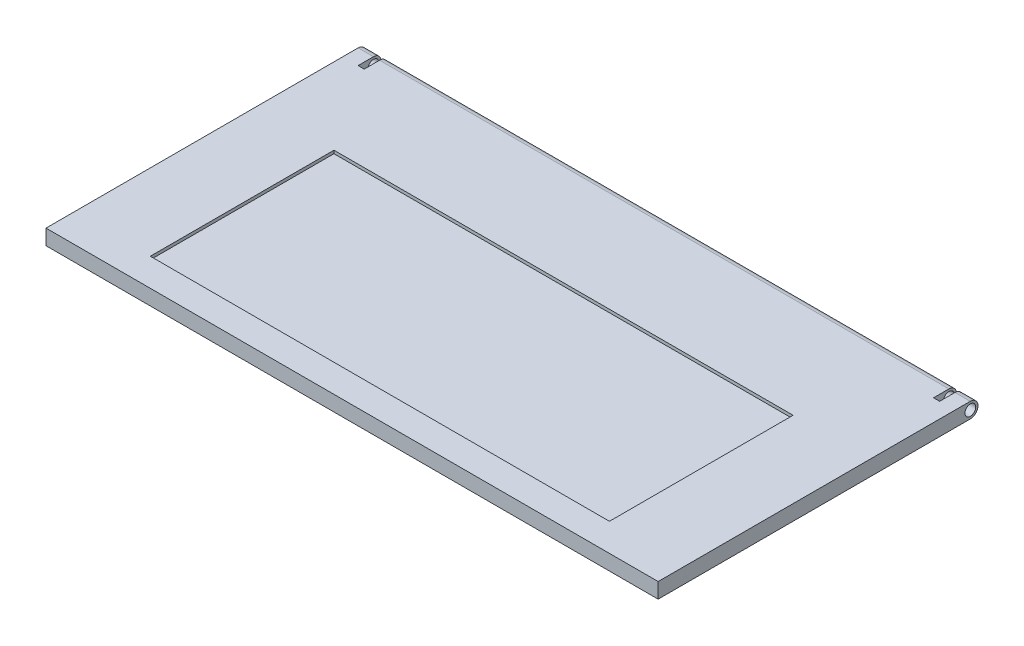
SolidWorks part; units mm, degrees
ref_plane "Front Plane" through (0, 0, 0) normal (0, 0, 1) x (1, 0, 0)
ref_plane "Top Plane" through (0, 0, 0) normal (0, 1, 0) x (1, 0, 0)
ref_plane "Right Plane" through (0, 0, 0) normal (1, 0, 0) x (0, 0, -1)
sketch "Sketch1" plane through (0, 0, 0) normal (0, 1, 0) x (1, 0, 0)
  line L1 (93, -47.5) -> (-93, -47.5)
  line L2 (93, -47.5) -> (93, 47.5)
  line L3 (93, 47.5) -> (-93, 47.5)
  line L4 (-93, -47.5) -> (-93, 47.5)
  line L5 (93, -47.5) -> (-93, 47.5) construction
  line L6 (93, 47.5) -> (-93, -47.5) construction
  point P0 (0, 0)
  dimension "D1" = 186
  dimension "D2" = 95
extrude "Boss-Extrude1" add sketch "Sketch1" along normal blind 5
sketch "Sketch2" plane through (0, 5, 0) normal (0, 1, 0) x (1, 0, 0)
  line L1 (75, -38.4183) -> (-75, -38.4183)
  line L2 (75, -38.4183) -> (75, 21.5817)
  line L3 (75, 21.5817) -> (-75, 21.5817)
  line L4 (-75, -38.4183) -> (-75, 21.5817)
  line L5 (75, -38.4183) -> (-75, 21.5817) construction
  line L6 (75, 21.5817) -> (-75, -38.4183) construction
  point P0 (0, -8.4183)
  dimension "D1" = 60
  dimension "D2" = 150
extrude "Cut-Extrude1" cut sketch "Sketch2" against normal blind 1
sketch "Sketch4" plane through (-93, 0, 0) normal (-1, 0, 0) x (0, 0, 1)
  line L0 (-47.5, 0) -> (-47.5, 5)
  line L1 (-47.5, 0) -> (-54.5, 0)
  line L2 (-47.5, 5) -> (-54.5, 5)
  arc A0 (-54.5, 0) -> (-54.5, 5) centre (-54.5, 2.5) cw
  circle A1 centre (-54.5, 2.5) radius 1.75
  dimension "D1" = 3.5
  dimension "D2" = 7
extrude "Boss-Extrude2" add sketch "Sketch4" against normal through all
sketch "Sketch5" plane through (0, 5, 0) normal (0, 1, 0) x (1, 0, 0)
  line L0 (0, 47.5) -> (0, -47.5)
  line L1 (93, 47.5) -> (-92, 47.5) construction
  line L2 (-93, -47.5) -> (93, -47.5) construction
ref_plane "Plane1" through (0, 0, 0) normal (-1, 0, 0) x (0, 0, 1)
sketch "Sketch6" plane through (-93, 0, 0) normal (-1, 0, 0) x (0, 0, 1)
  line L0 (-54.5, 0) -> (47.5, 0) construction
  line L1 (47.5, 5) -> (-49.4698, 5)
  line L2 (47.5, 5) -> (47.5, 0)
  line L3 (47.5, 0) -> (-49.4698, 0)
  line L4 (-49.4698, 5) -> (-49.4698, 0)
extrude "Boss-Extrude3" add sketch "Sketch6" along normal blind 2
mirror "Mirror2" about plane through (0, 0, 0) normal (-1, 0, 0) of "Boss-Extrude3"
sketch "Sketch7" plane through (-95, 0, 0) normal (-1, 0, 0) x (0, 0, 1)
  line L10 (47.5, 0) -> (47.5, 5) construction
  line L14 (-54.5, 5) -> (47.5, 5)
  line L15 (47.5, 0) -> (-54.5, 0)
  line L17 (47.5, 0) -> (47.5, 5)
  arc A1 (-54.5, 5) -> (-54.5, 0) centre (-54.5, 2.5) ccw construction
  arc A2 (-54.5, 5) -> (-54.5, 0) centre (-54.5, 2.5) ccw
  circle A3 centre (-54.5, 2.5) radius 1.75 construction
  circle A4 centre (-54.5, 2.5) radius 1.75
extrude "Boss-Extrude4" add sketch "Sketch7" along normal blind 5
mirror "Mirror3" about plane through (0, 0, 0) normal (-1, 0, 0) of "Boss-Extrude4"
